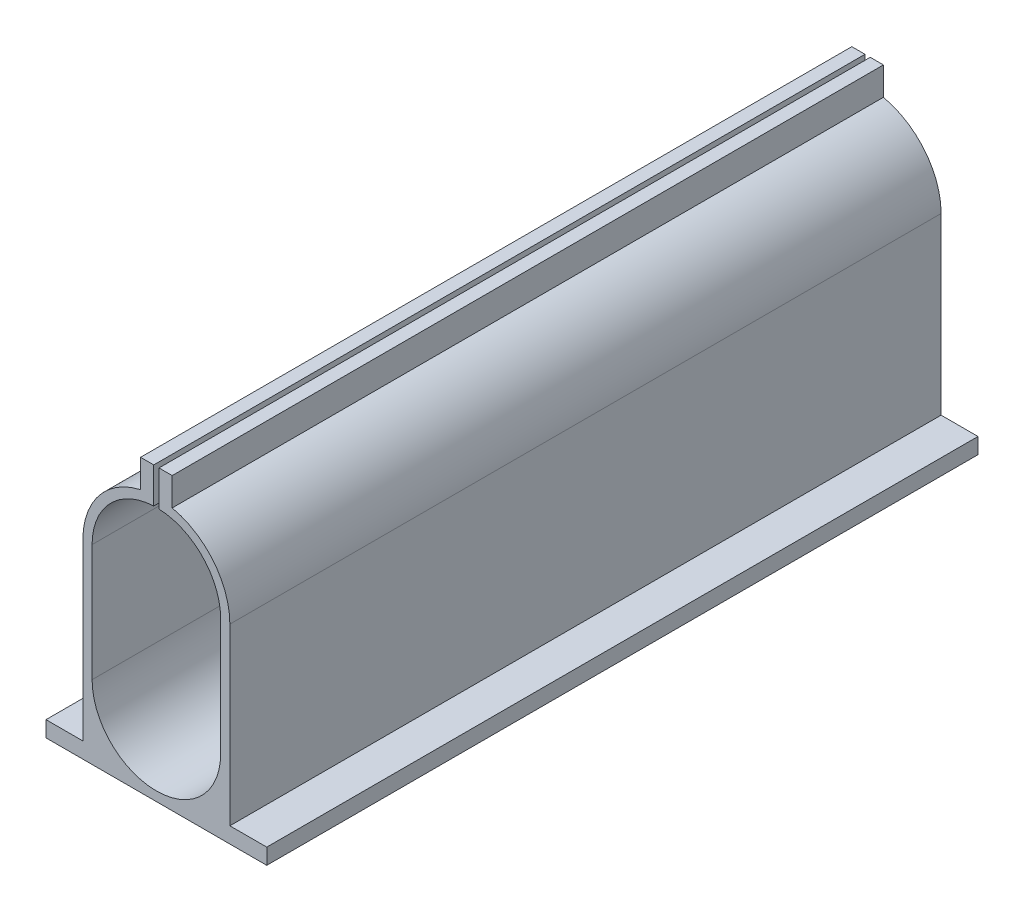
SolidWorks part; units mm, degrees
ref_plane "Front Plane" through (0, 0, 0) normal (0, 0, 1) x (1, 0, 0)
ref_plane "Top Plane" through (0, 0, 0) normal (0, 1, 0) x (1, 0, 0)
ref_plane "Right Plane" through (0, 0, 0) normal (1, 0, 0) x (0, 0, -1)
sketch "Sketch1" plane through (0, 0, 0) normal (0, 0, 1) x (1, 0, 0)
  line L2 (11.95, -11.1) -> (11.95, 11.1)
  line L3 (-11.95, 11.1) -> (-11.95, -11.1)
  line L4 (11.95, -11.1) -> (11.95, 11.1)
  line L5 (-11.95, 11.1) -> (-11.95, -11.1)
  line L6 (11.315, -11.1) -> (11.315, 11.1)
  line L7 (-11.315, 11.1) -> (-11.315, -11.1)
  line L8 (11.315, -11.1) -> (11.315, 11.1)
  line L9 (-11.315, 11.1) -> (-11.315, -11.1)
  arc A6 (11.95, 11.1) -> (-11.95, 11.1) centre (0, 11.1) ccw
  arc A7 (11.95, 11.1) -> (-11.95, 11.1) centre (0, 11.1) ccw
  arc A10 (-11.95, -11.1) -> (11.95, -11.1) centre (0, -11.1) ccw
  arc A11 (-11.95, -11.1) -> (11.95, -11.1) centre (0, -11.1) ccw
  arc A12 (-11.315, -11.1) -> (11.315, -11.1) centre (0, -11.1) ccw
  arc A13 (-11.315, -11.1) -> (11.315, -11.1) centre (0, -11.1) ccw
  arc A14 (11.315, 11.1) -> (-11.315, 11.1) centre (0, 11.1) ccw
  arc A15 (11.315, 11.1) -> (-11.315, 11.1) centre (0, 11.1) ccw
  dimension "D1" = 0
  dimension "D2" = 0
sketch "Sketch2" plane through (0, 0, 0) normal (0, 0, 1) x (1, 0, 0)
  line L4 (-11.95, 11.1) -> (-11.95, -11.1) construction
  line L5 (11.95, -11.1) -> (11.95, 11.1) construction
  line L6 (-13.95, 11.1) -> (-13.95, -11.1)
  line L7 (13.95, -11.1) -> (13.95, 11.1)
  line L8 (-13.95, -11.1) -> (-13.95, -22.05)
  line L9 (-13.95, -22.05) -> (-20.95, -22.05)
  line L10 (-20.95, -22.05) -> (-20.95, -25.05)
  line L11 (-20.95, -25.05) -> (20.95, -25.05)
  line L12 (20.95, -25.05) -> (20.95, -22.05)
  line L13 (20.95, -22.05) -> (13.95, -22.05)
  line L14 (13.95, -22.05) -> (13.95, -11.1)
  line L16 (12.2, -11.1) -> (12.2, 11.1)
  line L17 (-12.2, 11.1) -> (-12.2, -11.1)
  arc A4 (-11.95, -11.1) -> (11.95, -11.1) centre (0, -11.1) ccw construction
  arc A5 (11.95, 11.1) -> (-11.95, 11.1) centre (0, 11.1) ccw construction
  arc A6 (-13.95, -11.1) -> (13.95, -11.1) centre (0, -11.1) ccw construction
  arc A7 (13.95, 11.1) -> (-13.95, 11.1) centre (0, 11.1) ccw
  arc A8 (-11.95, -11.1) -> (11.95, -11.1) centre (0, -11.1) ccw construction
  arc A9 (11.95, 11.1) -> (-11.95, 11.1) centre (0, 11.1) ccw construction
  arc A10 (-12.2, -11.1) -> (12.2, -11.1) centre (0, -11.1) ccw
  arc A11 (12.2, 11.1) -> (-12.2, 11.1) centre (0, 11.1) ccw
  point P24 (-15.2, -21.7201)
  point P25 (25.4409, -25.3)
  dimension "D3" = 3
  dimension "D4" = 7
  dimension "D1" = 0.25
  dimension "D2" = 2
extrude "Boss-Extrude1" add sketch "Sketch2" along normal mid plane 135
sketch "Sketch5" plane through (0, 0, -67.5) normal (0, 0, -1) x (-1, 0, 0)
  line L7 (-13.95, 11.1) -> (-13.95, -22.05)
  line L8 (-13.95, -22.05) -> (-20.95, -22.05)
  line L9 (-20.95, -22.05) -> (-20.95, -25.05)
  line L10 (-20.95, -25.05) -> (20.95, -25.05)
  line L11 (20.95, -25.05) -> (20.95, -22.05)
  line L12 (20.95, -22.05) -> (13.95, -22.05)
  line L13 (13.95, -22.05) -> (13.95, 11.1)
  line L14 (-13.95, 11.1) -> (-13.95, -22.05)
  line L15 (-13.95, -22.05) -> (-20.95, -22.05)
  line L16 (-20.95, -22.05) -> (-20.95, -25.05)
  line L17 (-20.95, -25.05) -> (20.95, -25.05)
  line L18 (20.95, -25.05) -> (20.95, -22.05)
  line L19 (20.95, -22.05) -> (13.95, -22.05)
  line L20 (13.95, -22.05) -> (13.95, 11.1)
  arc A1 (13.95, 11.1) -> (-13.95, 11.1) centre (0, 11.1) ccw
  arc A2 (13.95, 11.1) -> (-13.95, 11.1) centre (0, 11.1) ccw
  dimension "D1" = 0
extrude "Boss-Extrude2" add sketch "Sketch5" against normal blind 3
sketch "Sketch6" plane through (0, 0, 67.5) normal (0, 0, 1) x (1, 0, 0)
  line L0 (0, 25.05) -> (0, 30.05) construction
  line L1 (-3, 23.3) -> (3, 23.3)
  line L2 (-3, 23.3) -> (-3, 30.05)
  line L3 (-3, 30.05) -> (3, 30.05)
  line L4 (3, 23.3) -> (3, 30.05)
  arc A2 (13.95, 11.1) -> (-13.95, 11.1) centre (0, 11.1) ccw construction
  arc A3 (12.2, 11.1) -> (-12.2, 11.1) centre (0, 11.1) ccw construction
  point P9 (0, 23.3)
  dimension "D1" = 6
  dimension "D2" = 5
extrude "Boss-Extrude3" add sketch "Sketch6" against normal up to surface (135 mm away) up to face at (0, -12.7687, -67.5)
sketch "Sketch7" plane through (0, 0, 67.5) normal (0, 0, 1) x (1, 0, 0)
  line L0 (3, 30.05) -> (-3, 30.05) construction
  line L1 (-0.5, 30.05) -> (0.5, 30.05)
  line L2 (-0.5, 30.05) -> (-0.5, -10)
  line L3 (-0.5, -10) -> (0.5, -10)
  line L4 (0.5, 30.05) -> (0.5, -10)
  line L5 (0, 0) -> (0, -10) construction
  point P6 (0, 30.05)
  point P7 (0, 30.05)
  dimension "D1" = 1
  dimension "D2" = 10
extrude "Cut-Extrude2" cut sketch "Sketch7" against normal through all
